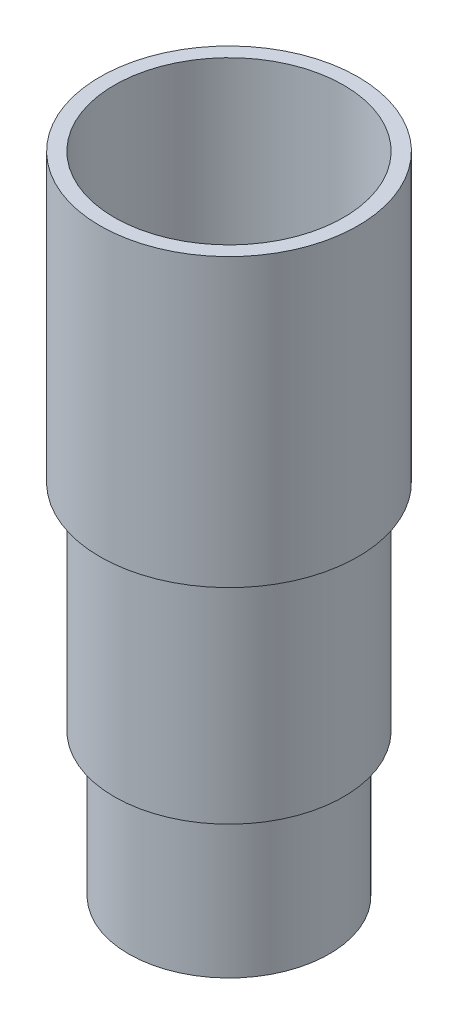
SolidWorks part; units mm, degrees
ref_plane "Front Plane" through (0, 0, 0) normal (0, 0, 1) x (1, 0, 0)
ref_plane "Top Plane" through (0, 0, 0) normal (0, 1, 0) x (1, 0, 0)
ref_plane "Right Plane" through (0, 0, 0) normal (1, 0, 0) x (0, 0, -1)
sketch "Sketch1" plane through (0, 0, 0) normal (0, 1, 0) x (1, 0, 0)
  line L1 (-10.16, -6.35) -> (10.16, -6.35)
  line L2 (-10.16, -6.35) -> (-10.16, 6.35)
  line L3 (-10.16, 6.35) -> (10.16, 6.35)
  line L4 (10.16, -6.35) -> (10.16, 6.35)
  line L5 (-10.16, -6.35) -> (10.16, 6.35) construction
  line L6 (-10.16, 6.35) -> (10.16, -6.35) construction
  circle A0 centre (0, 0) radius 15.24
  point P0 (0, 0)
extrude "Boss-Extrude1" add sketch "Sketch1" along normal blind 6.35
sketch "Sketch2" plane through (0, 0, 0) normal (0, 1, 0) x (1, 0, 0)
  circle A0 centre (0, 0) radius 15.24
  circle A1 centre (0, 0) radius 17.78
extrude "Boss-Extrude2" add sketch "Sketch2" along normal blind 25.4
sketch "Sketch5" plane through (0, 25.4, 0) normal (0, 1, 0) x (1, 0, 0)
  circle A0 centre (0, 0) radius 17.78
  circle A1 centre (0, 0) radius 20.32
extrude "Boss-Extrude3" add sketch "Sketch5" along normal blind 38.1 separate body
sketch "Sketch6" plane through (0, 63.5, 0) normal (0, 1, 0) x (1, 0, 0)
  circle A0 centre (0, 0) radius 20.32
  circle A1 centre (0, 0) radius 22.86
extrude "Boss-Extrude4" add sketch "Sketch6" along normal blind 50.8 separate body
